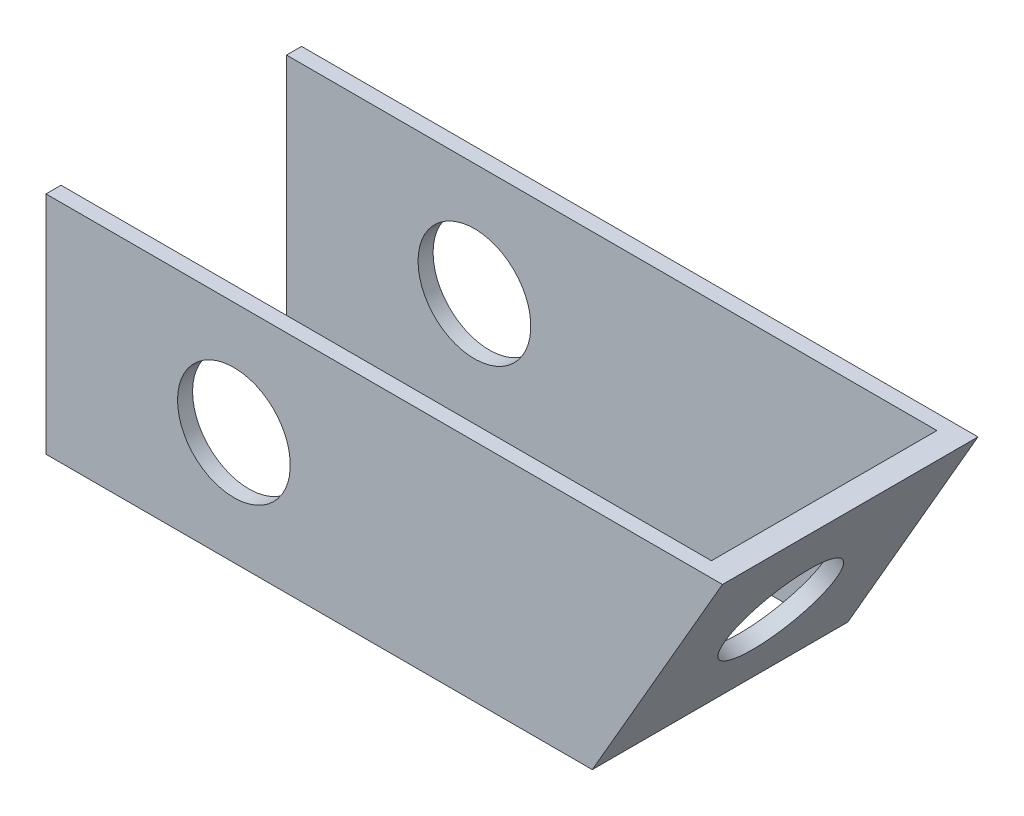
SolidWorks part; units mm, degrees
ref_plane "Plano frontal" through (0, 0, 0) normal (0, 0, 1) x (1, 0, 0)
ref_plane "Plano superior" through (0, 0, 0) normal (0, 1, 0) x (1, 0, 0)
ref_plane "Plano direito" through (0, 0, 0) normal (1, 0, 0) x (0, 0, -1)
sketch "Esboço1" plane through (0, 0, 0) normal (0, 0, 1) x (1, 0, 0)
  line L0 (45, 15) -> (27.6795, -15)
  line L1 (45, -15) -> (-45, -15)
  line L2 (45, -15) -> (45, 15)
  line L3 (45, 15) -> (-45, 15)
  line L4 (-45, -15) -> (-45, 15)
  line L5 (45, -15) -> (-45, 15) construction
  line L6 (45, 15) -> (-45, -15) construction
  point P0 (0, 0)
  dimension "D1" = 30
  dimension "D2" = 90
  dimension "D3" = 60
extrude "Ressalto-extrusão1" add sketch "Esboço1" along normal blind 34 contours L4 L1 L0 L3
shell "Casca1" thickness 2
sketch "Esboço2" plane through (0, 15, 0) normal (0, 1, 0) x (1, 0, 0)
  line L0 (-45, -34) -> (5, -34)
  line L1 (45, -34) -> (-45, -34) construction
  line L2 (5, -34) -> (5, -32)
  line L3 (5, 0) -> (5, -2)
  line L4 (45, 0) -> (-45, 0) construction
  line L6 (5, -32) -> (-45, -32)
  line L7 (5, -32) -> (5, -2)
  line L8 (5, -2) -> (-45, -2)
  line L9 (-45, -32) -> (-45, -2)
  line M6 (-45, 0) -> (-45, -34)
  dimension "D1" = 50
  dimension "D2" = 2
  dimension "D3" = 2
extrude "Corte-extrusão1" cut sketch "Esboço2" against normal blind 50 contours L7 L8 L6 M6
sketch "Esboço3" plane through (0, 0, 0) normal (0, 0, -1) x (-1, 0, 0)
  line L0 (45, 0) -> (20, 0)
  line L1 (45, -15) -> (45, 15) construction
  circle A0 centre (20, 0) radius 7.5
  dimension "D2" = 15
  dimension "D1" = 25
extrude "Corte-extrusão2" cut sketch "Esboço3" against normal blind 50
sketch "Esboço6" plane through (0, 13, 0) normal (0, -1, 0) x (-1, 0, 0)
  line L1 (-41.5359, -32) -> (-5, -32)
  line L2 (-41.5359, -32) -> (-41.5359, -2)
  line L3 (-41.5359, -2) -> (-5, -2)
  line L4 (-5, -32) -> (-5, -2)
extrude "Corte-extrusão5" cut sketch "Esboço6" against normal blind 2
sketch "Esboço7" plane through (0, -13, 0) normal (0, 1, 0) x (1, 0, 0)
  line L1 (26.5248, -32) -> (5, -32)
  line L2 (26.5248, -32) -> (26.5248, -2)
  line L3 (26.5248, -2) -> (5, -2)
  line L4 (5, -32) -> (5, -2)
extrude "Corte-extrusão6" cut sketch "Esboço7" against normal blind 2
sketch "Esboço8" plane through (25.5228, -14.7356, 0) normal (-0.866, 0.5, 0) x (0, 0, 1)
  line L0 (17, 32.0263) -> (17, 2.0041)
  line L1 (32, 32.0263) -> (2, 32.0263) construction
  line L2 (32, 2.0041) -> (2, 2.0041) construction
  circle A0 centre (17, 17.0152) radius 7.5
  dimension "D1" = 15
extrude "Corte-extrusão7" cut sketch "Esboço8" against normal blind 2 contours L0 A0 | L0 A0
